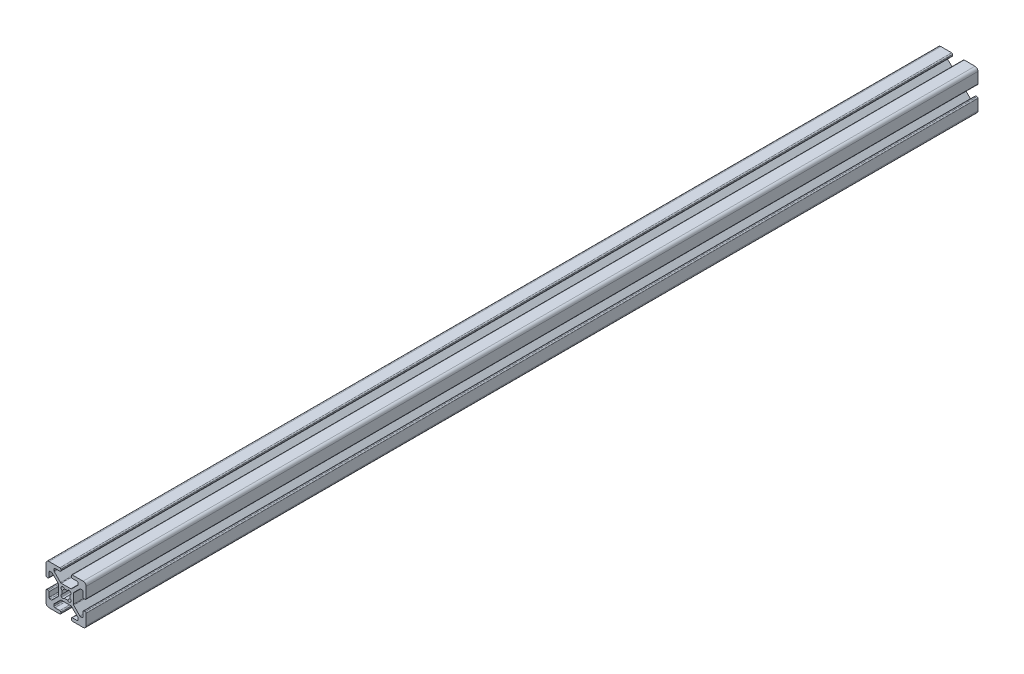
SolidWorks part; units mm, degrees
material "6105-T5 Aluminum"
ref_plane "Front Plane" through (0, 0, 0) normal (0, 0, 1) x (1, 0, 0)
ref_plane "Top Plane" through (0, 0, 0) normal (0, 1, 0) x (1, 0, 0)
ref_plane "Right Plane" through (0, 0, 0) normal (1, 0, 0) x (0, 0, -1)
sketch "Sketch1" plane through (0, 0, 0) normal (0, 0, 1) x (1, 0, 0)
  line L0 (9.492, 2.63) -> (9.008, 2.63)
  line L1 (8.5, 3.138) -> (8.5, 5.487)
  line L2 (10, 3.138) -> (10, 8.5)
  line L3 (3.655, -2.3839) -> (3.655, 2.3839)
  line L4 (7.2661, 5.995) -> (7.992, 5.995)
  line L5 (6.9069, 5.8462) -> (3.8038, 2.7431)
  line L6 (9.492, -2.63) -> (9.008, -2.63)
  line L7 (10, -3.138) -> (10, -8.5)
  line L8 (8.5, -3.138) -> (8.5, -5.487)
  line L9 (7.2661, -5.995) -> (7.992, -5.995)
  line L10 (6.9069, -5.8462) -> (3.8038, -2.7431)
  line L11 (2.1249, -2.3045) -> (2.3045, -2.1249)
  line L12 (-2.63, 9.492) -> (-2.63, 9.008)
  line L13 (-3.138, 10) -> (-8.5, 10)
  line L14 (-3.138, 8.5) -> (-5.487, 8.5)
  line L15 (2.3839, 3.655) -> (-2.3839, 3.655)
  line L16 (-5.995, 7.2661) -> (-5.995, 7.992)
  line L17 (-5.8462, 6.9069) -> (-2.7431, 3.8038)
  line L18 (2.63, 9.492) -> (2.63, 9.008)
  line L19 (3.138, 10) -> (8.5, 10)
  line L20 (3.138, 8.5) -> (5.487, 8.5)
  line L21 (5.995, 7.2661) -> (5.995, 7.992)
  line L22 (5.8462, 6.9069) -> (2.7431, 3.8038)
  line L23 (2.3045, 2.1249) -> (2.1249, 2.3045)
  line L24 (-9.492, -2.63) -> (-9.008, -2.63)
  line L25 (-10, -3.138) -> (-10, -8.5)
  line L26 (-8.5, -3.138) -> (-8.5, -5.487)
  line L27 (-3.655, 2.3839) -> (-3.655, -2.3839)
  line L28 (-7.2661, -5.995) -> (-7.992, -5.995)
  line L29 (-6.9069, -5.8462) -> (-3.8038, -2.7431)
  line L30 (-9.492, 2.63) -> (-9.008, 2.63)
  line L31 (-10, 3.138) -> (-10, 8.5)
  line L32 (-8.5, 3.138) -> (-8.5, 5.487)
  line L33 (-7.2661, 5.995) -> (-7.992, 5.995)
  line L34 (-6.9069, 5.8462) -> (-3.8038, 2.7431)
  line L35 (-2.1249, 2.3045) -> (-2.3045, 2.1249)
  line L36 (2.63, -9.492) -> (2.63, -9.008)
  line L37 (3.138, -10) -> (8.5, -10)
  line L38 (3.138, -8.5) -> (5.487, -8.5)
  line L39 (-2.3839, -3.655) -> (2.3839, -3.655)
  line L40 (5.995, -7.2661) -> (5.995, -7.992)
  line L41 (5.8462, -6.9069) -> (2.7431, -3.8038)
  line L42 (-2.63, -9.492) -> (-2.63, -9.008)
  line L43 (-3.138, -10) -> (-8.5, -10)
  line L44 (-3.138, -8.5) -> (-5.487, -8.5)
  line L45 (-5.995, -7.2661) -> (-5.995, -7.992)
  line L46 (-5.8462, -6.9069) -> (-2.7431, -3.8038)
  line L47 (-2.3045, -2.1249) -> (-2.1249, -2.3045)
  arc A0 (-0.804, -1.9351) -> (0.804, -1.9351) centre (0, 0) ccw
  arc A1 (8.5, 5.487) -> (7.992, 5.995) centre (7.992, 5.487) ccw
  arc A2 (7.2661, 5.995) -> (6.9069, 5.8462) centre (7.2661, 5.487) ccw
  arc A3 (3.8038, 2.7431) -> (3.655, 2.3839) centre (4.163, 2.3839) ccw
  arc A4 (3.655, -2.3839) -> (3.8038, -2.7431) centre (4.163, -2.3839) ccw
  arc A5 (6.9069, -5.8462) -> (7.2661, -5.995) centre (7.2661, -5.487) ccw
  arc A6 (7.992, -5.995) -> (8.5, -5.487) centre (7.992, -5.487) ccw
  arc A7 (9.008, -2.63) -> (8.5, -3.138) centre (9.008, -3.138) ccw
  arc A8 (10, -3.138) -> (9.492, -2.63) centre (9.492, -3.138) ccw
  arc A9 (9.492, 2.63) -> (10, 3.138) centre (9.492, 3.138) ccw
  arc A10 (8.5, 3.138) -> (9.008, 2.63) centre (9.008, 3.138) ccw
  arc A11 (0.804, -1.9351) -> (2.1249, -2.3045) centre (1.5684, -1.748) ccw
  arc A12 (2.3045, -2.1249) -> (1.9351, -0.804) centre (1.748, -1.5684) ccw
  arc A13 (-2.63, 9.492) -> (-3.138, 10) centre (-3.138, 9.492) ccw
  arc A14 (-3.138, 8.5) -> (-2.63, 9.008) centre (-3.138, 9.008) ccw
  arc A15 (1.9351, -0.804) -> (1.9351, 0.804) centre (0, 0) ccw
  arc A16 (-2.7431, 3.8038) -> (-2.3839, 3.655) centre (-2.3839, 4.163) ccw
  arc A17 (-5.487, 8.5) -> (-5.995, 7.992) centre (-5.487, 7.992) ccw
  arc A18 (-5.995, 7.2661) -> (-5.8462, 6.9069) centre (-5.487, 7.2661) ccw
  arc A19 (2.63, 9.008) -> (3.138, 8.5) centre (3.138, 9.008) ccw
  arc A20 (3.138, 10) -> (2.63, 9.492) centre (3.138, 9.492) ccw
  arc A21 (5.995, 7.992) -> (5.487, 8.5) centre (5.487, 7.992) ccw
  arc A22 (5.8462, 6.9069) -> (5.995, 7.2661) centre (5.487, 7.2661) ccw
  arc A23 (2.3839, 3.655) -> (2.7431, 3.8038) centre (2.3839, 4.163) ccw
  arc A24 (1.9351, 0.804) -> (2.3045, 2.1249) centre (1.748, 1.5684) ccw
  arc A25 (2.1249, 2.3045) -> (0.804, 1.9351) centre (1.5684, 1.748) ccw
  arc A26 (-9.492, -2.63) -> (-10, -3.138) centre (-9.492, -3.138) ccw
  arc A27 (-8.5, -3.138) -> (-9.008, -2.63) centre (-9.008, -3.138) ccw
  arc A28 (0.804, 1.9351) -> (-0.804, 1.9351) centre (0, 0) ccw
  arc A29 (-3.8038, -2.7431) -> (-3.655, -2.3839) centre (-4.163, -2.3839) ccw
  arc A30 (-8.5, -5.487) -> (-7.992, -5.995) centre (-7.992, -5.487) ccw
  arc A31 (-7.2661, -5.995) -> (-6.9069, -5.8462) centre (-7.2661, -5.487) ccw
  arc A32 (-9.008, 2.63) -> (-8.5, 3.138) centre (-9.008, 3.138) ccw
  arc A33 (-10, 3.138) -> (-9.492, 2.63) centre (-9.492, 3.138) ccw
  arc A34 (-7.992, 5.995) -> (-8.5, 5.487) centre (-7.992, 5.487) ccw
  arc A35 (-6.9069, 5.8462) -> (-7.2661, 5.995) centre (-7.2661, 5.487) ccw
  arc A36 (-3.655, 2.3839) -> (-3.8038, 2.7431) centre (-4.163, 2.3839) ccw
  arc A37 (-0.804, 1.9351) -> (-2.1249, 2.3045) centre (-1.5684, 1.748) ccw
  arc A38 (-2.3045, 2.1249) -> (-1.9351, 0.804) centre (-1.748, 1.5684) ccw
  arc A39 (2.63, -9.492) -> (3.138, -10) centre (3.138, -9.492) ccw
  arc A40 (3.138, -8.5) -> (2.63, -9.008) centre (3.138, -9.008) ccw
  arc A41 (-1.9351, 0.804) -> (-1.9351, -0.804) centre (0, 0) ccw
  arc A42 (2.7431, -3.8038) -> (2.3839, -3.655) centre (2.3839, -4.163) ccw
  arc A43 (5.487, -8.5) -> (5.995, -7.992) centre (5.487, -7.992) ccw
  arc A44 (5.995, -7.2661) -> (5.8462, -6.9069) centre (5.487, -7.2661) ccw
  arc A45 (-2.63, -9.008) -> (-3.138, -8.5) centre (-3.138, -9.008) ccw
  arc A46 (-3.138, -10) -> (-2.63, -9.492) centre (-3.138, -9.492) ccw
  arc A47 (-5.995, -7.992) -> (-5.487, -8.5) centre (-5.487, -7.992) ccw
  arc A48 (-5.8462, -6.9069) -> (-5.995, -7.2661) centre (-5.487, -7.2661) ccw
  arc A49 (-2.3839, -3.655) -> (-2.7431, -3.8038) centre (-2.3839, -4.163) ccw
  arc A50 (-1.9351, -0.804) -> (-2.3045, -2.1249) centre (-1.748, -1.5684) ccw
  arc A51 (-2.1249, -2.3045) -> (-0.804, -1.9351) centre (-1.5684, -1.748) ccw
  arc A52 (10, 8.5) -> (8.5, 10) centre (8.5, 8.5) ccw
  arc A53 (8.5, -10) -> (10, -8.5) centre (8.5, -8.5) ccw
  arc A54 (-10, -8.5) -> (-8.5, -10) centre (-8.5, -8.5) ccw
  arc A55 (-8.5, 10) -> (-10, 8.5) centre (-8.5, 8.5) ccw
extrude "Extrude1" add sketch "Sketch1" against normal blind 445
